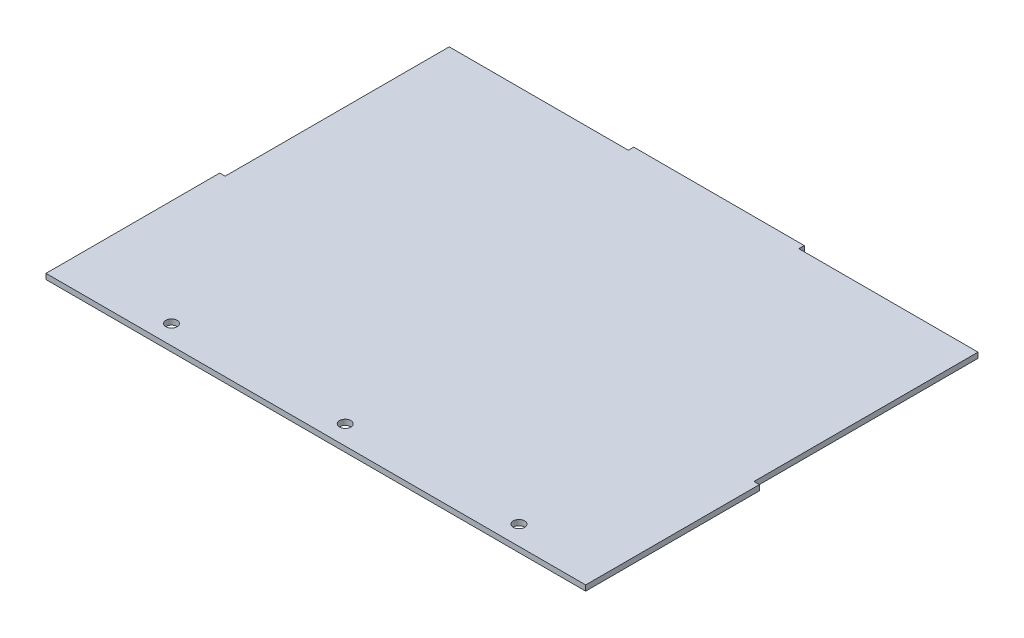
SolidWorks part; units mm, degrees
material "6061-T6 (SS)"
ref_plane "X-Y Datum" through (0, 0, 0) normal (0, 0, 1) x (1, 0, 0)
ref_plane "X-Z Datum" through (0, 0, 0) normal (0, 1, 0) x (1, 0, 0)
ref_plane "Y-Z Datum" through (0, 0, 0) normal (1, 0, 0) x (0, 0, -1)
sketch "Sketch1" plane through (0, 0, 0) normal (0, 0, 1) x (1, 0, 0)
  line L1 (-157.79, -1.5875) -> (157.79, -1.5875)
  line L2 (-157.79, -1.5875) -> (-157.79, 1.5875)
  line L3 (-157.79, 1.5875) -> (157.79, 1.5875)
  line L4 (157.79, -1.5875) -> (157.79, 1.5875)
  line L5 (-157.79, -1.5875) -> (157.79, 1.5875) construction
  line L6 (-157.79, 1.5875) -> (157.79, -1.5875) construction
  point P0 (0, 0)
  dimension "D1" = 315.58
  dimension "D2" = 3.175
extrude "Boss-Extrude1" add sketch "Sketch1" along normal blind 232.6
sketch "Sketch5" plane through (0, 1.5875, 0) normal (0, 1, 0) x (1, 0, 0)
  line L15 (-157.79, 0) -> (-154.615, 0)
  line L16 (-157.79, 0) -> (-157.79, -131)
  line L17 (-157.79, -131) -> (-154.615, -131)
  line L18 (-154.615, 0) -> (-154.615, -131)
  dimension "D3" = 3.175
  dimension "D4" = 131
extrude "Cut-Extrude2" cut sketch "Sketch5" against normal through all and the other way through all
mirror "Mirror1" about plane through (0, 0, 0) normal (1, 0, 0) of "Cut-Extrude2"
sketch "Sketch7" plane through (0, -1.5875, 0) normal (0, -1, 0) x (1, 0, 0)
  line L0 (110.4954, 221.3083) -> (104.4954, 221.3083) construction
  circle A0 centre (107.4954, 221.3083) radius 3.302
  dimension "D1" = 6.604
extrude "Cut-Extrude3" cut sketch "Sketch7" against normal through all
pattern_linear "LPattern1" count 3 spacing 101.6 along (-1, 0, 0) of "Cut-Extrude3"
sketch "Sketch8" plane through (0, 0, 0) normal (0, 0, -1) x (-1, 0, 0)
  line L0 (-154.615, -1.5875) -> (-154.615, 1.5875) construction
  line L4 (-154.615, 1.5875) -> (154.615, 1.5875) construction
  line L5 (49.84, 1.5875) -> (-49.84, 1.5875)
  line L6 (49.84, 1.5875) -> (49.84, -1.5875)
  line L7 (49.84, -1.5875) -> (-49.84, -1.5875)
  line L8 (-49.84, 1.5875) -> (-49.84, -1.5875)
  line L9 (154.615, -1.5875) -> (-154.615, -1.5875) construction
  dimension "D1" = 104.775
extrude "Boss-Extrude2" add sketch "Sketch8" along normal blind 3.175
